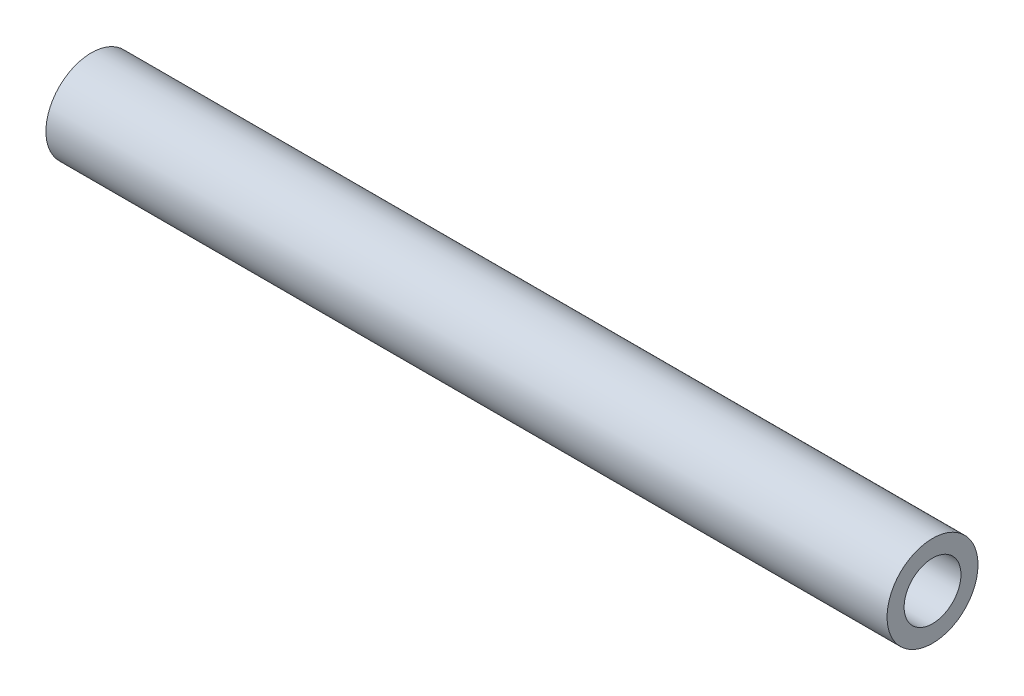
SolidWorks part; units mm, degrees
material "Alumina"
ref_plane "Front Plane" through (0, 0, 0) normal (0, 0, 1) x (1, 0, 0)
ref_plane "Top Plane" through (0, 0, 0) normal (0, 1, 0) x (1, 0, 0)
ref_plane "Right Plane" through (0, 0, 0) normal (1, 0, 0) x (0, 0, -1)
sketch "Sketch1" plane through (0, 0, 0) normal (1, 0, 0) x (0, 0, -1)
  circle A0 centre (0, 0) radius 4
  dimension "D1" = 8
extrude "Boss-Extrude1" add sketch "Sketch1" along normal mid plane 74
sketch "Sketch2" plane through (37, 0, 0) normal (1, 0, 0) x (0, 0, -1)
  circle A0 centre (0, 0) radius 2.5
  dimension "5" = 5
extrude "Cut-Extrude1" cut sketch "Sketch2" against normal blind 15
cosmetic thread "Cosmetic Thread1"
mirror "Mirror1" about plane through (0, 0, 0) normal (1, 0, 0) of "Cut-Extrude1"
cosmetic thread "Cosmetic Thread2"
